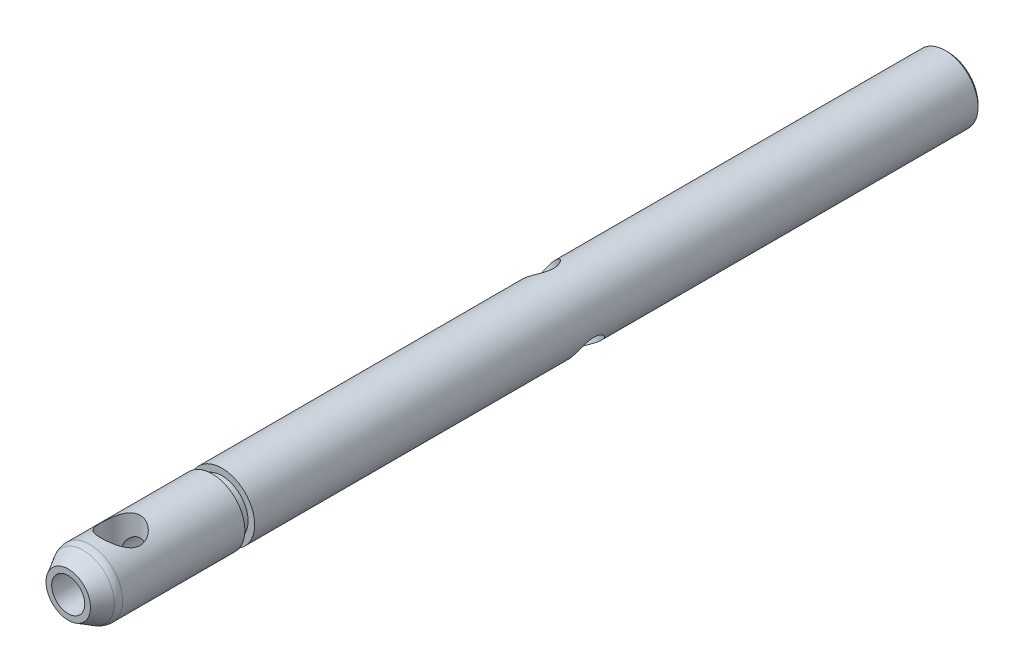
SolidWorks part; units mm, degrees
ref_plane "Front Plane" through (0, 0, 0) normal (0, 0, 1) x (1, 0, 0)
ref_plane "Top Plane" through (0, 0, 0) normal (0, 1, 0) x (1, 0, 0)
ref_plane "Right Plane" through (0, 0, 0) normal (1, 0, 0) x (0, 0, -1)
ref_plane "Plane1" through (0, 0, 0) normal (0, -1, 0) x (1, 0, 0)
sketch "Sketch1" plane through (0, 0, 0) normal (0, -1, 0) x (1, 0, 0)
  line L0 (1.7, 11.75) -> (0, 11.75)
  line L1 (0, 11.75) -> (0, -55.5)
  line L2 (0, -55.5) -> (2.5, -55.5)
  line L3 (2.5, -55.5) -> (2.5, 0)
  line L4 (2.5, 0) -> (2, 0)
  line L5 (2, 0) -> (2, 0.75)
  line L6 (2, 0.75) -> (2.5, 0.75)
  line L7 (2.5, 0.75) -> (2.5, 10.3644)
  line L8 (2.5, 10.3644) -> (1.7, 11.75)
  line L9 (0, 11.75) -> (0, -55.5) construction
  line L10 (55, 0) -> (-55, 0) construction
  line L11 (0, -55) -> (0, 55) construction
  point P9 (0.85, 11.75)
  dimension "D1" = 55.5
  dimension "D2" = 11.75
  dimension "D3" = 9.6144
  dimension "D4" = 0.75
  dimension "D5" = 0.5
  dimension "D6" = 120
  dimension "D8" = 2.5
revolve "Revolve1" add sketch "Sketch1" angle 360 about L9
ref_plane "Plane4" through (0, 0, -52.5) normal (0, 0, 1) x (1, 0, 0)
sketch "Sketch2" plane through (0, 0, -52.5) normal (0, 0, -1) x (-1, 0, 0)
  line L0 (1.5, -2) -> (-1.5, -2)
  arc A0 (-1.5, -2) -> (1.5, -2) centre (0, 0) ccw
extrude "Cut-Extrude1" cut sketch "Sketch2" against normal blind 4
hole_wizard "Ø3.0 (3) Diameter Hole1" positions "3DSketch1" profile "Sketch3" hole size "Ø3.0" standard "ANSI Metric"
sketch3d "3DSketch1"
  point P0 (0, -2.5, 7.75)
sketch "Sketch3" plane through (0, -2.5, 7.75) normal (1, 0, 0) x (0, 0, -1)
  line L0 (0, 0) -> (0, 5)
  line L1 (0, 5) -> (1.5, 5)
  line L2 (1.5, 5) -> (1.5, 0)
  line L5 (1.5, 0) -> (0, 0)
  line L11 (0, -6.35) -> (0, 107.95) construction
  dimension "Thru Hole Dia." = 3
  dimension "Thru Hole Depth" = 5
hole_wizard "M2 Clearance Hole1" positions "Sketch5" profile "Sketch4" hole size "M2" standard "ANSI Metric"
sketch "Sketch5" plane through (0, 0, 11.75) normal (0, 0, 1) x (1, 0, 0)
  point P0 (0, 0)
sketch "Sketch4" plane through (0, 0, 11.75) normal (1, 0, 0) x (0, -1, 0)
  line L0 (0, 0) -> (0, 2.5)
  line L1 (0, 2.5) -> (1.2645, 2.5)
  line L2 (1.2645, 2.5) -> (1.2645, 0)
  line L5 (1.2645, 0) -> (0, 0)
  line L11 (0, -6.35) -> (0, 107.95) construction
  dimension "Thru Hole Dia." = 2.529
  dimension "Thru Hole Depth" = 2.5
ref_plane "Plane3" through (0, 0, 6.632) normal (0, 0, 1) x (1, 0, 0)
hole_wizard "Ø2.0 (2) Diameter Hole1" positions "Sketch7" profile "Sketch6" hole size "Ø2.0" standard "ANSI Metric"
sketch "Sketch7" plane through (0, 0, 6.632) normal (0, 0, 1) x (1, 0, 0)
  point P0 (0, 0)
sketch "Sketch6" plane through (0, 0, 6.632) normal (1, 0, 0) x (0, -1, 0)
  line L0 (0, 0) -> (0, 1.632)
  line L1 (0, 1.632) -> (1, 1.632)
  line L2 (1, 1.632) -> (1, 0)
  line L5 (1, 0) -> (0, 0)
  line L10 (0, 1.632) -> (-1, 1.632) construction
  line L11 (0, -6.35) -> (0, 107.95) construction
  dimension "Hole Dia." = 2
  dimension "Hole Depth" = 1.632
  dimension "Drill Angle" = 180
hole_wizard "M2 Clearance Hole2" positions "Sketch9" profile "Sketch8" hole size "M2" standard "ANSI Metric"
sketch "Sketch9" plane through (0, 0, -55.5) normal (0, 0, -1) x (-1, 0, 0)
  point P0 (0, 0)
sketch "Sketch8" plane through (0, 0, -55.5) normal (1, 0, 0) x (0, 1, 0)
  line L0 (0, 0) -> (0, 5.5)
  line L1 (0, 5.5) -> (1.2645, 5.5)
  line L2 (1.2645, 5.5) -> (1.2645, 0)
  line L5 (1.2645, 0) -> (0, 0)
  line L10 (0, 5.5) -> (-1.2645, 5.5) construction
  line L11 (0, -6.35) -> (0, 107.95) construction
  dimension "Hole Dia." = 2.529
  dimension "Hole Depth" = 5.5
  dimension "Drill Angle" = 180
hole_wizard "M2 Clearance Hole3" positions "3DSketch2" profile "Sketch10" hole size "M2" standard "ANSI Metric"
sketch3d "3DSketch2"
  point P0 (1.7678, -1.7678, -26)
  dimension "D1" = 26
  dimension "D2" = 1.7678
sketch "Sketch10" plane through (1.7678, -1.7678, -26) normal (0, 0, 1) x (0.7071, 0.7071, 0)
  line L0 (0, 0) -> (0, 6.0355)
  line L1 (0, 6.0355) -> (1.2645, 6.0355)
  line L2 (1.2645, 6.0355) -> (1.2645, 0)
  line L5 (1.2645, 0) -> (0, 0)
  line L11 (0, -6.35) -> (0, 107.95) construction
  dimension "Thru Hole Dia." = 2.529
  dimension "Thru Hole Depth" = 6.0355
chamfer "Chamfer1" distance 0.2 angle 45 1 edges at (-2.5, 0, -55.5)
fillet "Fillet1" radius 1 1 edges at (-2.5, 0, 10.3644)
sketch "Sketch11" plane through (0, -2, 0) normal (0, -1, 0) x (1, 0, 0)
  line L0 (-1.5, -52.5) -> (1.5, -48.5) construction
  line L1 (1.5, -52.5) -> (-1.5, -48.5) construction
  line L2 (-1.5, -48.5) -> (-1.5, -52.5) construction
  circle A0 centre (0, -50.5) radius 1.5 construction
